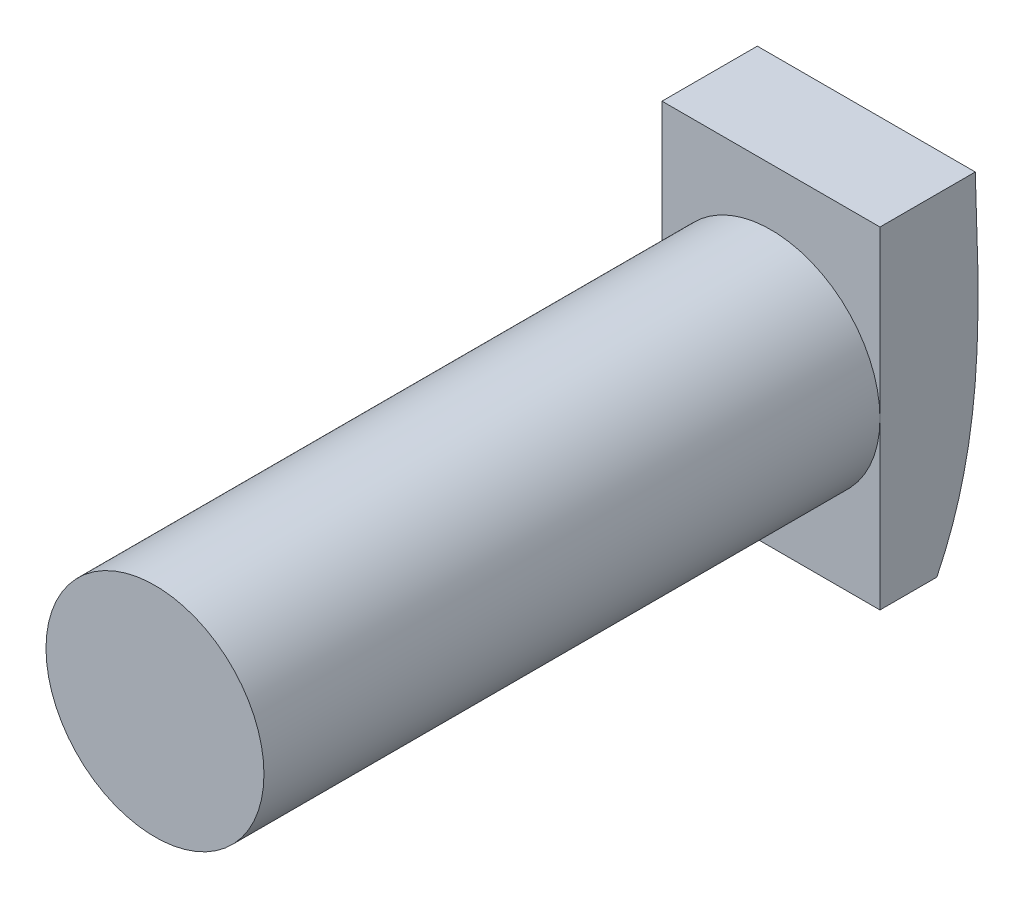
SolidWorks part; units mm, degrees
ref_plane "Front Plane" through (0, 0, 0) normal (0, 0, 1) x (1, 0, 0)
ref_plane "Top Plane" through (0, 0, 0) normal (0, 1, 0) x (1, 0, 0)
ref_plane "Right Plane" through (0, 0, 0) normal (1, 0, 0) x (0, 0, -1)
sketch "Sketch1" plane through (0, 0, 0) normal (0, 0, 1) x (1, 0, 0)
  circle A0 centre (0, 0) radius 2.3
  dimension "D1" = 4.6
extrude "Boss-Extrude1" add sketch "Sketch1" along normal blind 13
sketch "Sketch2" plane through (0, 0, 0) normal (0, 0, -1) x (-1, 0, 0)
  line L1 (-2.3, -3.5) -> (2.3, -3.5)
  line L2 (-2.3, -3.5) -> (-2.3, 3.5)
  line L3 (-2.3, 3.5) -> (2.3, 3.5)
  line L4 (2.3, -3.5) -> (2.3, 3.5)
  line L5 (-2.3, -3.5) -> (2.3, 3.5) construction
  line L6 (-2.3, 3.5) -> (2.3, -3.5) construction
  circle A0 centre (0, 0) radius 2.3 construction
  point P0 (0, 0)
  dimension "D1" = 7
extrude "Boss-Extrude2" add sketch "Sketch2" along normal blind 3
sketch "Sketch3" plane through (2.3, 0, 0) normal (1, 0, 0) x (0, 0, -1)
  line L0 (3, 3.5) -> (0, 3.5) construction
  line L1 (3, -3.5) -> (0, -3.5) construction
  line L2 (0, 0) -> (0, -3.5) construction
  line L3 (0, 3.5) -> (0, 0) construction
  line L4 (1.2, -3.5) -> (3, -3.5)
  line L5 (3, -3.5) -> (3, 3.5)
  line L6 (3, 3.5) -> (2.0115, 3.5)
  line L7 (3, 3.5) -> (0, 3.5) construction
  spline S0 degree 3 poles (1.2, -3.5) (2.2675, -1.3344) (2.0824, 1.1824) (2.0115, 3.5) knots 0 0 0 0 1 1 1 1
  dimension "D1" = 1.2
  dimension "D2" = 2
extrude "Cut-Extrude1" cut sketch "Sketch3" against normal up to vertex (4.6 mm away)
